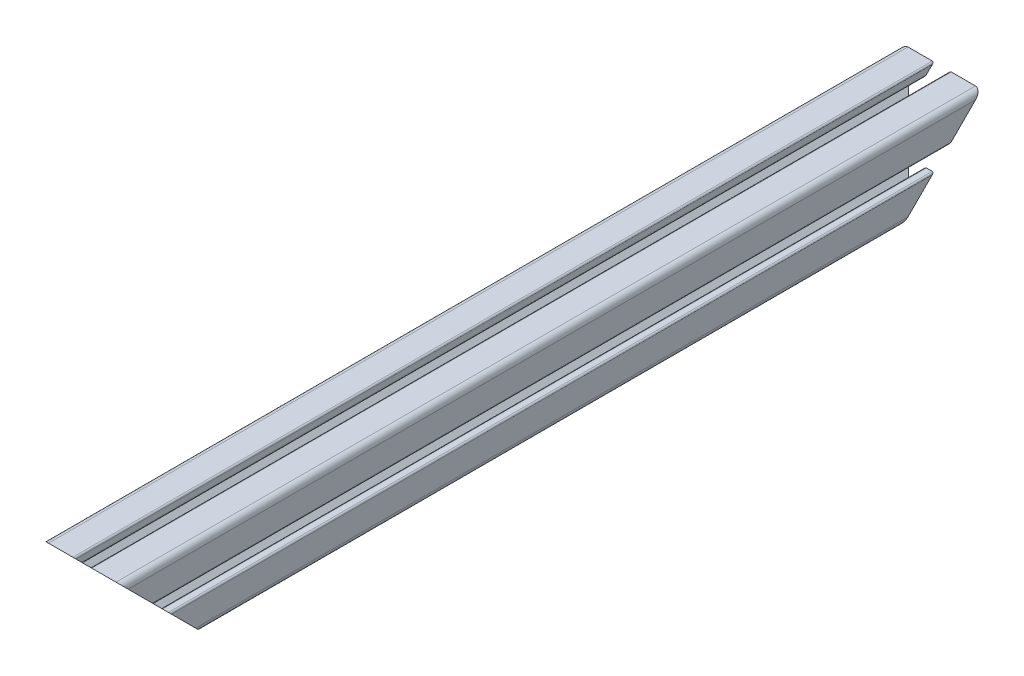
SolidWorks part; units mm, degrees
ref_plane "Front Plane" through (0, 0, 0) normal (0, 0, 1) x (1, 0, 0)
ref_plane "Top Plane" through (0, 0, 0) normal (0, 1, 0) x (1, 0, 0)
ref_plane "Right Plane" through (0, 0, 0) normal (1, 0, 0) x (0, 0, -1)
sketch "Sketch1" plane through (0, 0, 0) normal (0, 0, 1) x (1, 0, 0)
  line L0 (0, 20) -> (0, -20) construction
  line L1 (-20, 0) -> (20, 0) construction
  line L2 (-20, 16.952) -> (-20, 4.7625)
  line L3 (-16.952, 20) -> (-4.7625, 20)
  line L4 (-4.0005, 19.238) -> (-4.0005, 16.2662)
  line L5 (-4.7625, 15.5042) -> (-10.4856, 15.5042)
  line L6 (-11.0244, 14.2034) -> (-5.456, 8.6351)
  line L7 (-14.2034, 11.0244) -> (-8.6351, 5.456)
  line L8 (-15.5042, 10.4856) -> (-15.5042, 4.7625)
  line L9 (-16.2662, 4.0005) -> (-19.238, 4.0005)
  line L10 (0, 0) -> (-20, 20) construction
  line L11 (-3.3367, 7.7572) -> (3.3367, 7.7572)
  line L12 (-7.7572, 3.3367) -> (-7.7572, -3.3367)
  line L13 (16.2662, 4.0005) -> (19.238, 4.0005)
  line L14 (15.5042, 10.4856) -> (15.5042, 4.7625)
  line L15 (20, 16.952) -> (20, 4.7625)
  line L16 (16.952, 20) -> (4.7625, 20)
  line L17 (4.0005, 19.238) -> (4.0005, 16.2662)
  line L18 (4.7625, 15.5042) -> (10.4856, 15.5042)
  line L19 (7.7572, 3.3367) -> (7.7572, -3.3367)
  line L20 (11.0244, 14.2034) -> (5.456, 8.6351)
  line L21 (14.2034, 11.0244) -> (8.6351, 5.456)
  line L22 (-16.2662, -4.0005) -> (-19.238, -4.0005)
  line L23 (-15.5042, -10.4856) -> (-15.5042, -4.7625)
  line L24 (-14.2034, -11.0244) -> (-8.6351, -5.456)
  line L25 (-11.0244, -14.2034) -> (-5.456, -8.6351)
  line L26 (-4.7625, -15.5042) -> (-10.4856, -15.5042)
  line L27 (-4.0005, -19.238) -> (-4.0005, -16.2662)
  line L28 (-16.952, -20) -> (-4.7625, -20)
  line L29 (-20, -16.952) -> (-20, -4.7625)
  line L30 (20, -16.952) -> (20, -4.7625)
  line L31 (16.952, -20) -> (4.7625, -20)
  line L32 (4.0005, -19.238) -> (4.0005, -16.2662)
  line L33 (4.7625, -15.5042) -> (10.4856, -15.5042)
  line L34 (11.0244, -14.2034) -> (5.456, -8.6351)
  line L35 (14.2034, -11.0244) -> (8.6351, -5.456)
  line L36 (15.5042, -10.4856) -> (15.5042, -4.7625)
  line L37 (16.2662, -4.0005) -> (19.238, -4.0005)
  line L38 (-3.3367, -7.7572) -> (3.3367, -7.7572)
  circle A0 centre (0, 0) radius 3.4036
  arc A1 (-20, 16.952) -> (-16.952, 20) centre (-16.952, 16.952) cw
  arc A2 (-14.2034, 11.0244) -> (-15.5042, 10.4856) centre (-14.7422, 10.4856) ccw
  arc A3 (-10.4856, 15.5042) -> (-11.0244, 14.2034) centre (-10.4856, 14.7422) ccw
  arc A4 (-4.7625, 20) -> (-4.0005, 19.238) centre (-4.7625, 19.238) cw
  arc A5 (-20, 4.7625) -> (-19.238, 4.0005) centre (-19.238, 4.7625) ccw
  arc A6 (-15.5042, 4.7625) -> (-16.2662, 4.0005) centre (-16.2662, 4.7625) cw
  arc A7 (-4.0005, 16.2662) -> (-4.7625, 15.5042) centre (-4.7625, 16.2662) cw
  arc A8 (-3.3367, 7.7572) -> (-5.456, 8.6351) centre (-3.3367, 10.7544) cw
  arc A9 (-7.7572, 3.3367) -> (-8.6351, 5.456) centre (-10.7544, 3.3367) ccw
  arc A10 (15.5042, 4.7625) -> (16.2662, 4.0005) centre (16.2662, 4.7625) ccw
  arc A11 (20, 4.7625) -> (19.238, 4.0005) centre (19.238, 4.7625) cw
  arc A12 (20, 16.952) -> (16.952, 20) centre (16.952, 16.952) ccw
  arc A13 (4.7625, 20) -> (4.0005, 19.238) centre (4.7625, 19.238) ccw
  arc A14 (4.0005, 16.2662) -> (4.7625, 15.5042) centre (4.7625, 16.2662) ccw
  arc A15 (3.3367, 7.7572) -> (5.456, 8.6351) centre (3.3367, 10.7544) ccw
  arc A16 (7.7572, 3.3367) -> (8.6351, 5.456) centre (10.7544, 3.3367) cw
  arc A17 (14.2034, 11.0244) -> (15.5042, 10.4856) centre (14.7422, 10.4856) cw
  arc A18 (10.4856, 15.5042) -> (11.0244, 14.2034) centre (10.4856, 14.7422) cw
  arc A19 (-7.7572, -3.3367) -> (-8.6351, -5.456) centre (-10.7544, -3.3367) cw
  arc A20 (-3.3367, -7.7572) -> (-5.456, -8.6351) centre (-3.3367, -10.7544) ccw
  arc A21 (-4.0005, -16.2662) -> (-4.7625, -15.5042) centre (-4.7625, -16.2662) ccw
  arc A22 (-15.5042, -4.7625) -> (-16.2662, -4.0005) centre (-16.2662, -4.7625) ccw
  arc A23 (-20, -4.7625) -> (-19.238, -4.0005) centre (-19.238, -4.7625) cw
  arc A24 (-4.7625, -20) -> (-4.0005, -19.238) centre (-4.7625, -19.238) ccw
  arc A25 (-10.4856, -15.5042) -> (-11.0244, -14.2034) centre (-10.4856, -14.7422) cw
  arc A26 (-14.2034, -11.0244) -> (-15.5042, -10.4856) centre (-14.7422, -10.4856) cw
  arc A27 (-20, -16.952) -> (-16.952, -20) centre (-16.952, -16.952) ccw
  arc A28 (20, -16.952) -> (16.952, -20) centre (16.952, -16.952) cw
  arc A29 (14.2034, -11.0244) -> (15.5042, -10.4856) centre (14.7422, -10.4856) ccw
  arc A30 (10.4856, -15.5042) -> (11.0244, -14.2034) centre (10.4856, -14.7422) ccw
  arc A31 (4.7625, -20) -> (4.0005, -19.238) centre (4.7625, -19.238) cw
  arc A32 (20, -4.7625) -> (19.238, -4.0005) centre (19.238, -4.7625) ccw
  arc A33 (15.5042, -4.7625) -> (16.2662, -4.0005) centre (16.2662, -4.7625) cw
  arc A34 (4.0005, -16.2662) -> (4.7625, -15.5042) centre (4.7625, -16.2662) cw
  arc A35 (3.3367, -7.7572) -> (5.456, -8.6351) centre (3.3367, -10.7544) cw
  arc A36 (7.7572, -3.3367) -> (8.6351, -5.456) centre (10.7544, -3.3367) ccw
  point P29 (-20, 4.0005)
  point P32 (-15.5042, 4.0005)
  point P36 (-4.5782, 7.7572)
  point P68 (0, 7.7572)
  dimension "D4" = 6.8072
  dimension "D5" = 3.048
  dimension "D6" = 0.762
  dimension "D9" = 0.762
  dimension "D10" = 0.762
  dimension "D11" = 4.4958
  dimension "D13" = 2.9972
  dimension "D1" = 40
  dimension "D2" = 40
  dimension "D3" = 12.2428
  dimension "D7" = 8.001
  dimension "D8" = 4.4958
extrude "Extrude1" add sketch "Sketch1" along normal mid plane 431.8
ref_plane "Plane1" through (-16.952, 20, 215.9) normal (-1, 0, 0) x (0, 0, 1)
sketch "Sketch3" plane through (-16.952, 20, 215.9) normal (-1, 0, 0) x (0, 0, 1)
  line L0 (0, 0) -> (-40, -40)
  line L1 (0, -40) -> (-431.8, -40) construction
  line L2 (-40, -40) -> (0, -40)
  line L3 (0, -40) -> (0, 0)
  dimension "D1" = 45
extrude "Cut-Extrude1" cut sketch "Sketch3" against normal through all
sketch "Sketch4" plane through (-16.952, 0, 0) normal (1, 0, 0) x (0, 0, -1)
  line L0 (-215.9, 20) -> (-215.9, -20)
  line L1 (-215.9, -20) -> (-175.9, -20)
  line L2 (-175.9, -20) -> (-215.9, 20)
extrude "Cut-Extrude2" cut sketch "Sketch4" against normal up to surface (3.048 mm away) up to face at (-20, 10.8572, 0)
sketch "Sketch9" plane through (-16.952, 20, 215.9) normal (-1, 0, 0) x (0, 0, 1)
  line L0 (-431.8, 0) -> (-391.8, -40)
  line L2 (-40, -40) -> (-431.8, -40) construction
  line L3 (-431.8, 0) -> (-431.8, -40)
  line L4 (-391.8, -40) -> (-431.8, -40)
  dimension "D1" = 45
extrude "Cut-Extrude5" cut sketch "Sketch9" against normal up to surface (36.952 mm away) up to face at (20, 10.8572, -4.5714)
sketch "Sketch11" plane through (-16.952, 0, 0) normal (1, 0, 0) x (0, 0, -1)
  line L0 (175.9, -20) -> (215.9, 20)
  line L1 (215.9, 20) -> (215.9, -20)
  line L2 (215.9, -20) -> (175.9, -20)
extrude "Cut-Extrude6" cut sketch "Sketch11" against normal up to surface (3.048 mm away) up to face at (-20, -10.8572, -15.4286)
equation "\"D2@Sketch1\" = \"D1@Sketch1\""
